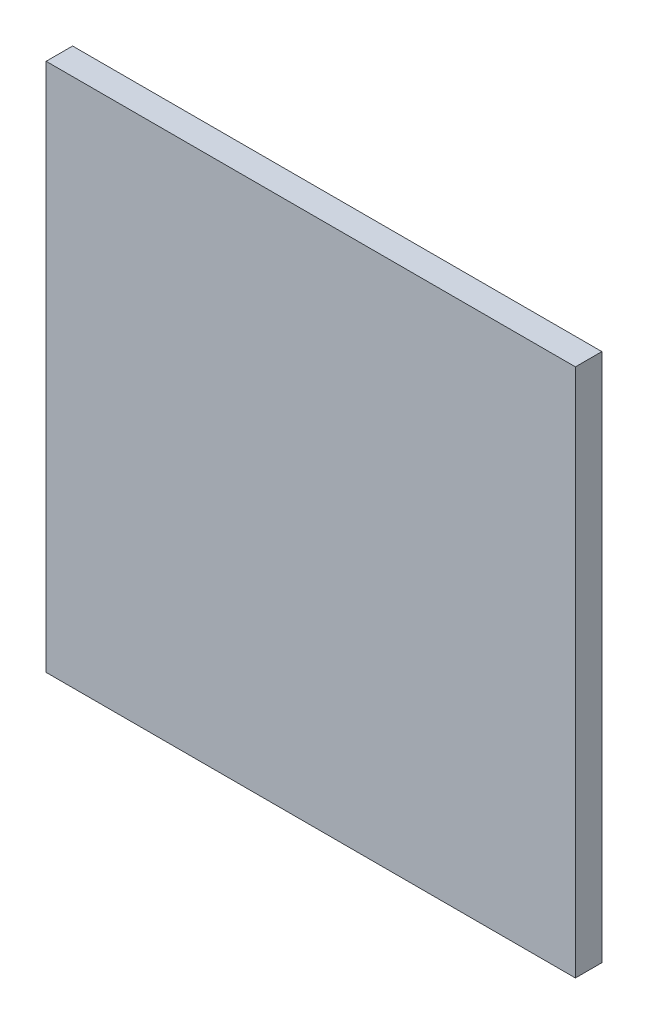
SolidWorks part; units mm, degrees
ref_plane "Спереди" through (0, 0, 0) normal (0, 0, 1) x (1, 0, 0)
ref_plane "Сверху" through (0, 0, 0) normal (0, 1, 0) x (1, 0, 0)
ref_plane "Справа" through (0, 0, 0) normal (1, 0, 0) x (0, 0, -1)
sketch "Эскиз1" plane through (0, 0, 0) normal (0, 0, 1) x (1, 0, 0)
  line L1 (10, -10) -> (-10, -10)
  line L2 (10, -10) -> (10, 10)
  line L3 (10, 10) -> (-10, 10)
  line L4 (-10, -10) -> (-10, 10)
  line L5 (10, -10) -> (-10, 10) construction
  line L6 (10, 10) -> (-10, -10) construction
  point P0 (0, 0)
extrude "Бобышка-Вытянуть1" add sketch "Эскиз1" along normal blind 1
sketch "Эскиз2" plane through (0, 0, 1) normal (0, 0, 1) x (1, 0, 0)
  circle A25 centre (-3, -3) radius 1.55
  circle A26 centre (-1.5, -3) radius 1.55
  circle A27 centre (0, -3) radius 1.55
  circle A28 centre (1.5, -3) radius 1.55
  circle A29 centre (3, -3) radius 1.55
  circle A30 centre (-1.5, -1.5) radius 1.55
  circle A31 centre (0, -1.5) radius 1.55
  circle A32 centre (1.5, -1.5) radius 1.55
  circle A33 centre (3, -1.5) radius 1.55
  circle A34 centre (-1.5, 0) radius 1.55
  circle A35 centre (0, 0) radius 1.55
  circle A36 centre (1.5, 0) radius 1.55
  circle A37 centre (3, 0) radius 1.55
  circle A38 centre (-1.5, 1.5) radius 1.55
  circle A39 centre (0, 1.5) radius 1.55
  circle A40 centre (1.5, 1.5) radius 1.55
  circle A41 centre (3, 1.5) radius 1.55
  circle A42 centre (-1.5, 3) radius 1.55
  circle A43 centre (0, 3) radius 1.55
  circle A44 centre (1.5, 3) radius 1.55
  circle A45 centre (3, 3) radius 1.55
  circle A46 centre (-3, -1.5) radius 1.55
  circle A47 centre (-3, 0) radius 1.55
  circle A48 centre (-3, 1.5) radius 1.55
  circle A49 centre (-3, 3) radius 1.55
  point P0 (0, 0)
  point P3 (0, 0)
  dimension "D1" = 3.1
